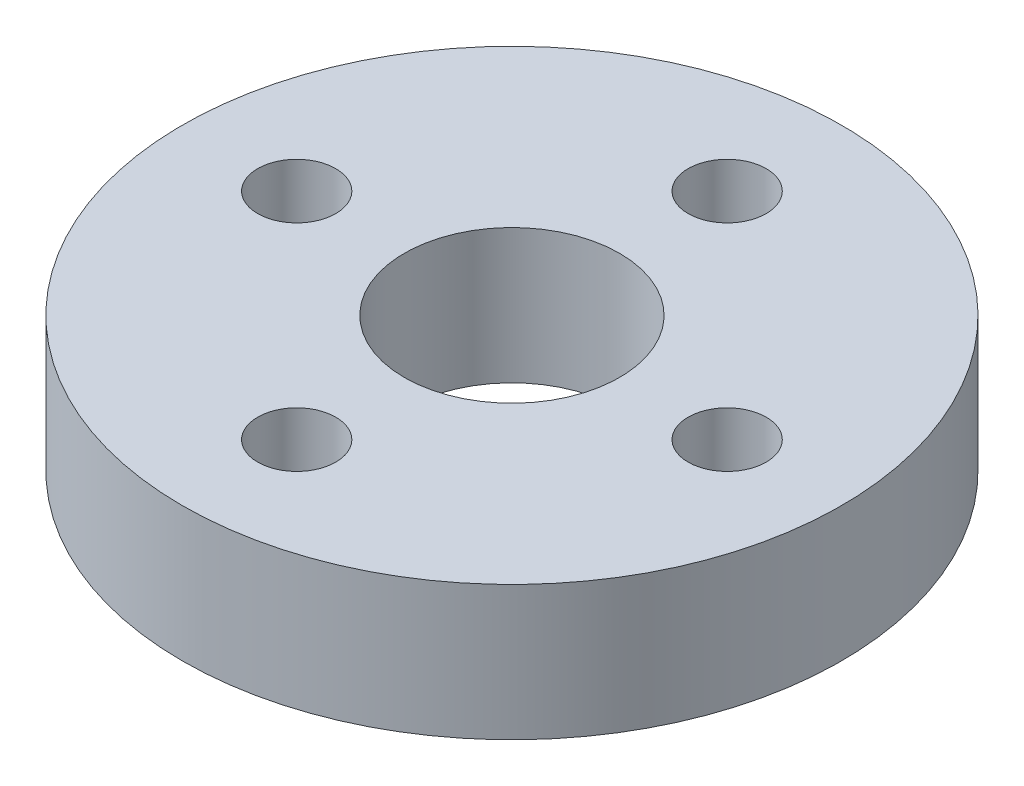
SolidWorks part; units mm, degrees
ref_plane "前视基准面" through (0, 0, 0) normal (0, 0, 1) x (1, 0, 0)
ref_plane "上视基准面" through (0, 0, 0) normal (0, 1, 0) x (1, 0, 0)
ref_plane "右视基准面" through (0, 0, 0) normal (1, 0, 0) x (0, 0, -1)
sketch "草图1" plane through (0, 0, 0) normal (0, 1, 0) x (1, 0, 0)
  line L1 (8, 0) -> (0, 8) construction
  line L2 (0, 8) -> (-8, 0) construction
  line L3 (-8, 0) -> (0, -8) construction
  line L4 (0, -8) -> (8, 0) construction
  circle A0 centre (0, 0) radius 12.25
  circle A1 centre (0, 0) radius 4
  circle A2 centre (0, 0) radius 8 construction
  circle A3 centre (0, 0) radius 5.6569 construction
  circle A4 centre (0, 8) radius 1.45
  circle A5 centre (8, 0) radius 1.45
  circle A6 centre (0, -8) radius 1.45
  circle A7 centre (-8, 0) radius 1.45
  dimension "D1" = 24.5
  dimension "D2" = 8
  dimension "D3" = 16
  dimension "D4" = 2.9
extrude "凸台-拉伸1" add sketch "草图1" along normal blind 5
